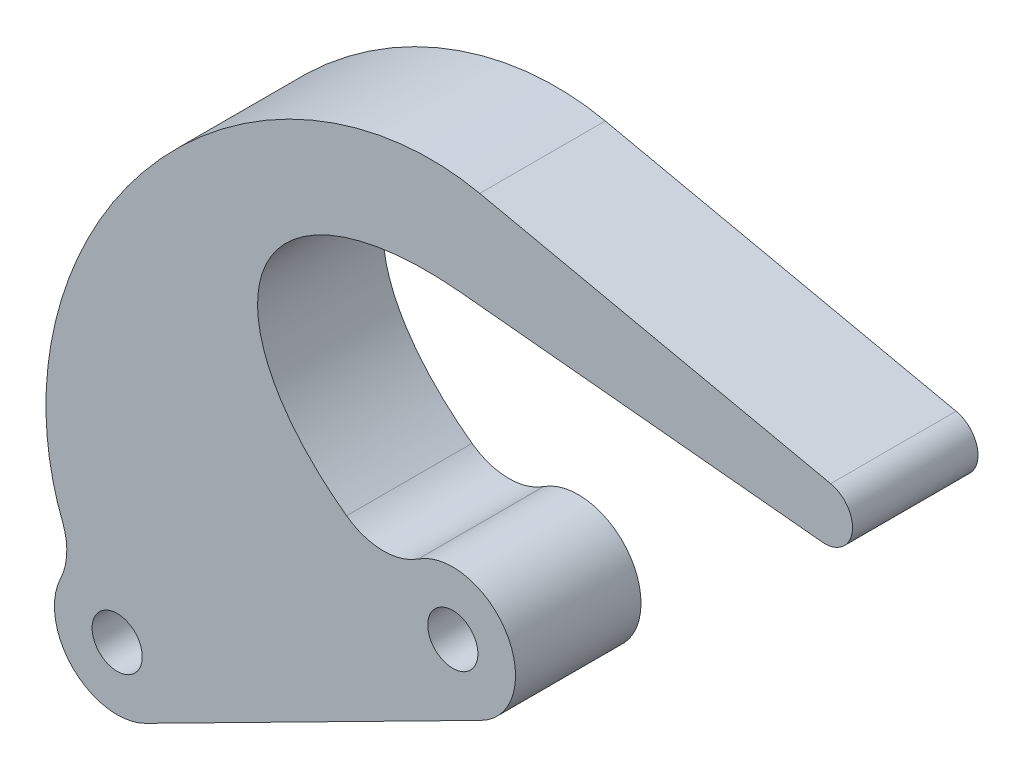
SolidWorks part; units mm, degrees
ref_plane "Front Plane" through (0, 0, 0) normal (0, 0, 1) x (1, 0, 0)
ref_plane "Top Plane" through (0, 0, 0) normal (0, 1, 0) x (1, 0, 0)
ref_plane "Right Plane" through (0, 0, 0) normal (1, 0, 0) x (0, 0, -1)
sketch "Sketch1" plane through (0, 0, 0) normal (0, 0, 1) x (1, 0, 0)
  line L5 (1.9976, 14.7467) -> (28.7481, 28.3266)
  line L6 (28.6337, 64.643) -> (56.5994, 58.5916)
  line L13 (55.9154, 54.2274) -> (27.0963, 57.0559)
  circle A11 centre (-0.2657, 19.2051) radius 2
  circle A12 centre (26.4848, 32.785) radius 2
  arc A13 (28.7481, 28.3266) -> (23.7248, 36.9543) centre (26.4848, 32.785) ccw
  arc A15 (18.0184, 37.084) -> (23.7248, 36.9543) centre (20.9649, 41.1235) ccw
  arc A16 (55.9154, 54.2274) -> (56.5994, 58.5916) centre (56.1315, 56.4293) ccw
  arc A17 (-4.7719, 21.3718) -> (-4.6249, 25.3684) centre (-9.278, 23.5385) ccw
  arc A18 (-4.7719, 21.3718) -> (1.9976, 14.7467) centre (-0.2657, 19.2051) ccw
  ellipse E0 centre (30.2747, 44.1708) end of major axis (11.2983, 50.4873) minor radius 12 (27.0963, 57.0559) -> (18.0184, 37.084) ccw
  ellipse E1 centre (17.5124, 40.3175) end of major axis (-0.2657, 19.2051) minor radius 20 (28.6337, 64.643) -> (-4.6249, 25.3684) ccw
  point P44 (61.9999, 53.8584)
  dimension "D2" = 30
extrude "Boss-Extrude1" add sketch "Sketch1" along normal blind 10
